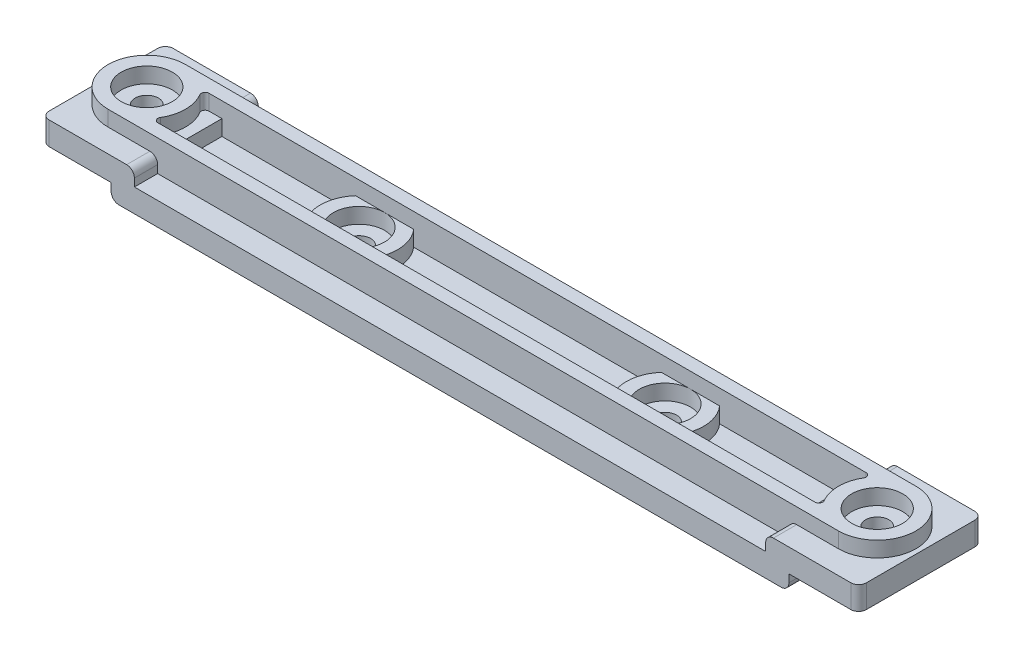
SolidWorks part; units mm, degrees
ref_plane "前视基准面" through (0, 0, 0) normal (0, 0, 1) x (1, 0, 0)
ref_plane "上视基准面" through (0, 0, 0) normal (0, 1, 0) x (1, 0, 0)
ref_plane "右视基准面" through (0, 0, 0) normal (1, 0, 0) x (0, 0, -1)
sketch "草图1" plane through (0, 0, 0) normal (0, 1, 0) x (1, 0, 0)
  line L1 (-52.75, -8) -> (52.75, -8)
  line L2 (-52.75, -8) -> (-52.75, 8)
  line L3 (-52.75, 8) -> (52.75, 8)
  line L4 (52.75, -8) -> (52.75, 8)
  line L5 (-52.75, -8) -> (52.75, 8) construction
  line L6 (-52.75, 8) -> (52.75, -8) construction
  point P0 (0, 0)
  dimension "D1" = 105.5
  dimension "D2" = 16
extrude "凸台-拉伸1" add sketch "草图1" along normal blind 5
sketch "草图2" plane through (0, 0, 8) normal (0, 0, 1) x (1, 0, 0)
  line L0 (-52.75, 5) -> (52.75, 5) construction
  line L1 (-40.75, 3) -> (40.75, 3)
  line L2 (-40.75, 3) -> (-40.75, 5)
  line L3 (-40.75, 5) -> (40.75, 5)
  line L4 (40.75, 3) -> (40.75, 5)
  line L5 (-40.75, 3) -> (40.75, 5) construction
  line L6 (-40.75, 5) -> (40.75, 3) construction
  line L7 (-52.75, 0) -> (52.75, 0) construction
  point P0 (0, 4)
  dimension "D1" = 3
  dimension "D2" = 81.5
extrude "切除-拉伸1" cut sketch "草图2" against normal blind 16
sketch "草图5" plane through (0, 0, 0) normal (0, -1, 0) x (1, 0, 0)
  line L0 (0, 10.6564) -> (0, -11.8801) construction
  line L1 (-45.65, 0) -> (45.65, 0) construction
  line L2 (-19.75, -1.5) -> (19.75, -1.5) construction
  circle A0 centre (-47.15, 0) radius 1.5
  circle A1 centre (47.15, 0) radius 1.5
  circle A2 centre (-19.75, 0) radius 1.5
  circle A3 centre (19.75, 0) radius 1.5
  point P9 (0, 0)
  point P16 (0, -1.5)
  dimension "D1" = 3
  dimension "D2" = 3
  dimension "D4" = 3
  dimension "D5" = 3
  dimension "D3" = 91.3
  dimension "D6" = 39.5
extrude "切除-拉伸2" cut sketch "草图5" against normal blind 5
sketch "草图6" plane through (0, 0, 0) normal (0, -1, 0) x (1, 0, 0)
  line L0 (-47.15, 0) -> (47.15, 0) construction
  line L1 (-47.15, 5) -> (47.15, 5) construction
  line L2 (-47.15, -5) -> (47.15, -5) construction
  line L3 (-47.15, 3.3) -> (47.15, 3.3) construction
  line L4 (-47.15, -3.3) -> (47.15, -3.3) construction
  line L5 (-47.15, 5) -> (47.15, 5)
  line L6 (47.15, -5) -> (-47.15, -5)
  line L7 (-42.4161, 3.3) -> (42.4161, 3.3)
  line L8 (-42.4161, -3.3) -> (42.4161, -3.3)
  arc A0 (-47.15, 5) -> (-47.15, -5) centre (-47.15, 0) ccw construction
  arc A1 (47.15, -5) -> (47.15, 5) centre (47.15, 0) ccw
  arc A2 (47.15, -3.3) -> (47.15, 3.3) centre (47.15, 0) ccw construction
  arc A3 (-47.15, 3.3) -> (-47.15, -3.3) centre (-47.15, 0) ccw construction
  circle A4 centre (-47.15, 0) radius 3.3
  arc A5 (-42.8464, -2.5455) -> (-42.8464, 2.5455) centre (-47.15, 0) ccw
  circle A6 centre (47.15, 0) radius 3.3
  arc A7 (42.8464, 2.5455) -> (42.8464, -2.5455) centre (47.15, 0) ccw
  arc A8 (-47.15, 5) -> (-47.15, -5) centre (-47.15, 0) ccw
  arc A9 (47.15, -5) -> (47.15, 5) centre (47.15, 0) ccw
  arc A10 (-42.4161, -3.3) -> (-42.8464, -2.5455) centre (-42.4161, -2.8) cw
  arc A11 (-42.4161, 3.3) -> (-42.8464, 2.5455) centre (-42.4161, 2.8) ccw
  arc A12 (42.4161, -3.3) -> (42.8464, -2.5455) centre (42.4161, -2.8) ccw
  arc A13 (42.8464, 2.5455) -> (42.4161, 3.3) centre (42.4161, 2.8) ccw
  point P4 (0, 0)
  point P27 (-43.3937, -3.3)
  point P30 (-43.3937, 3.3)
  point P33 (43.3937, -3.3)
  point P36 (43.3937, 3.3)
  dimension "D3" = 0.5
  dimension "D1" = 10
  dimension "D2" = 1.7
extrude "凸台-拉伸3" add sketch "草图6" against normal blind 7 contours L5 A8 L6 A1 A13 A7 A12 L8 A10 A5 A11 L7 A4 A6
sketch "草图7" plane through (0, 0, 0) normal (0, -1, 0) x (1, 0, 0)
  circle A0 centre (-19.75, 0) radius 5
  circle A1 centre (-19.75, 0) radius 3.3
  circle A2 centre (19.75, 0) radius 5
  circle A3 centre (19.75, 0) radius 3.3
extrude "凸台-拉伸4" add sketch "草图7" against normal blind 5
sketch "草图8" plane through (0, 0, 8) normal (0, 0, 1) x (1, 0, 0)
  line L0 (-52.75, 0) -> (-43.75, 0)
  line L1 (-52.75, 0) -> (52.75, 0) construction
  line L2 (-52.75, 0) -> (-52.75, 2)
  line L3 (-52.75, 5) -> (-52.75, 0) construction
  line L4 (-52.75, 2) -> (-43.75, 2)
  line L5 (-43.75, 2) -> (-43.75, 0)
  line L6 (-43.85, 7) -> (-50.45, 7) construction
  line L7 (0, 11.5106) -> (0, -3.6741) construction
  line L8 (43.75, 2) -> (43.75, 0)
  line L9 (52.75, 2) -> (43.75, 2)
  line L10 (52.75, 0) -> (52.75, 2)
  line L11 (52.75, 0) -> (43.75, 0)
  dimension "D1" = 9
  dimension "D2" = 5
extrude "切除-拉伸3" cut sketch "草图8" against normal blind 16
fillet "圆角1" radius 1 6 edges at (43.75, 0, 0) (-43.75, 0, 0) (52.75, 3.5, -8) (-52.75, 3.5, -8) (52.75, 3.5, 8) (-52.75, 3.5, 8)
fillet "圆角2" radius 1 4 edges at (40.75, 5, -6.5) (40.75, 5, 6.5) (-40.75, 5, 6.5) (-40.75, 5, -6.5)
